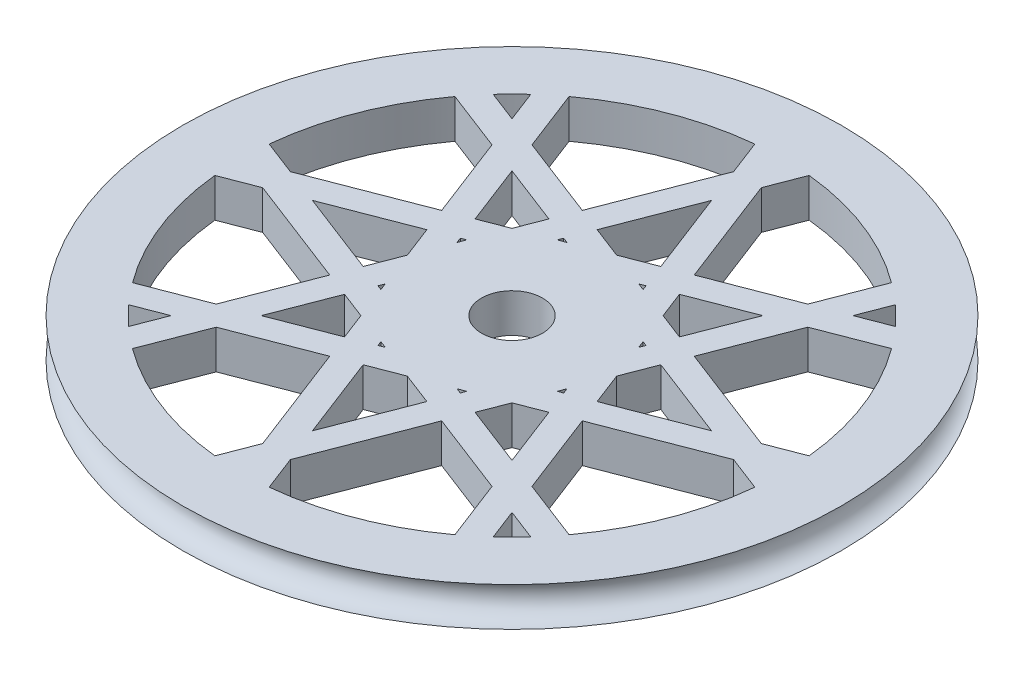
SolidWorks part; units mm, degrees
ref_plane "Front Plane" through (0, 0, 0) normal (0, 0, 1) x (1, 0, 0)
ref_plane "Top Plane" through (0, 0, 0) normal (0, 1, 0) x (1, 0, 0)
ref_plane "Right Plane" through (0, 0, 0) normal (1, 0, 0) x (0, 0, -1)
sketch "Sketch1" plane through (0, 0, 0) normal (0, 0, 1) x (1, 0, 0)
  line L0 (0, 0) -> (0, 3.175)
  line L1 (0, 0) -> (3.175, 0)
  line L2 (0, 3.175) -> (3.175, 3.175)
  line L4 (-22.225, 12.7691) -> (-22.225, -11.1448)
  line L5 (3.175, 3.175) -> (4.7625, 3.175)
  line L7 (3.175, 0) -> (4.7625, 0)
  arc A0 (4.7625, 3.175) -> (4.7625, 0) centre (4.7625, 1.5875) ccw
  point P1 (3.175, 1.5875)
  dimension "D4" = 1.5875
  dimension "D1" = 25.4
  dimension "D2" = 3.175
  dimension "D3" = 3.175
revolve "Revolve2" add sketch "Sketch1" angle 360 about L4
sketch "Sketch2" plane through (0, 0, 0) normal (0, 1, 0) x (1, 0, 0)
  circle A0 centre (-22.225, 0) radius 2.5
  circle A1 centre (-22.225, 0) radius 8
extrude "Boss-Extrude1" add sketch "Sketch2" along normal up to surface (3.175 mm away) separate body up to face at (-49.2125, 3.175, 0)
sketch "Sketch4" plane through (0, 0, 0) normal (0, -1, 0) x (1, 0, 0)
  line L1 (-22.225, -16.3446) -> (-35.4286, 17.8778)
  line L2 (-23.3594, -19.2848) -> (-37.1525, 16.4657)
  line L3 (-41.5098, 1.1344) -> (-5.7593, 14.9275)
  line L4 (-38.5696, 0) -> (-4.3472, 13.2036)
  line L5 (-4.3472, -13.2036) -> (-38.5696, 0)
  line L6 (-23.3594, -19.2848) -> (-24.4506, -22.1133)
  line L7 (-21.0906, -19.2848) -> (-7.2974, 16.4657)
  line L9 (-9.0214, 17.8778) -> (-22.225, -16.3446)
  line L11 (-21.0906, -19.2848) -> (-19.9994, -22.1133)
  line L12 (-41.5098, -1.1344) -> (-5.7593, -14.9276)
  line L13 (-41.5098, -1.1344) -> (-44.3383, -2.2256)
  line L14 (-41.5098, 1.1344) -> (-44.3383, 2.2256)
  line L15 (-21.0906, 19.2848) -> (-7.2975, -16.4657)
  line L16 (-22.225, 16.3446) -> (-9.0214, -17.8778)
  line L17 (-35.4286, -17.8778) -> (-22.225, 16.3446)
  line L18 (-23.3594, 19.2848) -> (-37.1526, -16.4657)
  line L19 (-23.3594, 19.2848) -> (-24.4506, 22.1133)
  line L20 (-21.0906, 19.2848) -> (-19.9994, 22.1133)
  line L21 (-2.9402, -1.1344) -> (-38.6907, -14.9275)
  line L22 (-5.8804, 0) -> (-40.1028, -13.2036)
  line L23 (-40.1028, 13.2036) -> (-5.8804, 0)
  line L24 (-2.9402, 1.1344) -> (-38.6907, 14.9276)
  line L25 (-2.9402, 1.1344) -> (-0.1117, 2.2256)
  line L26 (-2.9402, -1.1344) -> (-0.1117, -2.2256)
  circle A0 centre (-22.225, 0) radius 22.225 construction
  arc A1 (-7.2974, 16.4657) -> (-9.0214, 17.8778) centre (-22.225, 0) ccw
  arc A2 (-24.4506, -22.1133) -> (-19.9994, -22.1133) centre (-22.225, 0) ccw
  arc A3 (-35.4286, 17.8778) -> (-37.1525, 16.4657) centre (-22.225, 0) ccw
  arc A4 (-4.3472, 13.2036) -> (-5.7593, 14.9275) centre (-22.225, 0) ccw
  arc A5 (-5.7593, -14.9276) -> (-4.3472, -13.2036) centre (-22.225, 0) ccw
  arc A6 (-44.3383, 2.2256) -> (-44.3383, -2.2256) centre (-22.225, 0) ccw
  arc A7 (-9.0214, -17.8778) -> (-7.2975, -16.4657) centre (-22.225, 0) ccw
  arc A8 (-37.1526, -16.4657) -> (-35.4286, -17.8778) centre (-22.225, 0) ccw
  arc A9 (-19.9994, 22.1133) -> (-24.4506, 22.1133) centre (-22.225, 0) ccw
  arc A10 (-40.1028, -13.2036) -> (-38.6907, -14.9275) centre (-22.225, 0) ccw
  arc A11 (-38.6907, 14.9276) -> (-40.1028, 13.2036) centre (-22.225, 0) ccw
  arc A12 (-0.1117, -2.2256) -> (-0.1117, 2.2256) centre (-22.225, 0) ccw
  dimension "D1" = 2.1167
  dimension "D2" = 4
extrude "Boss-Extrude2" add sketch "Sketch4" against normal up to surface (3.175 mm away) contours L12 A5 L5 L4 A4 L3 L14 A6 L13 | L2 A3 L1 L9 A1 L7 L11 A2 L6 | L17 L16 A7 L15 L20 A9 L19 L18 A8 | L24 A11 L23 L22 A10 L21 L26 A12 L25 up to face at (-49.2125, 3.175, 0)
